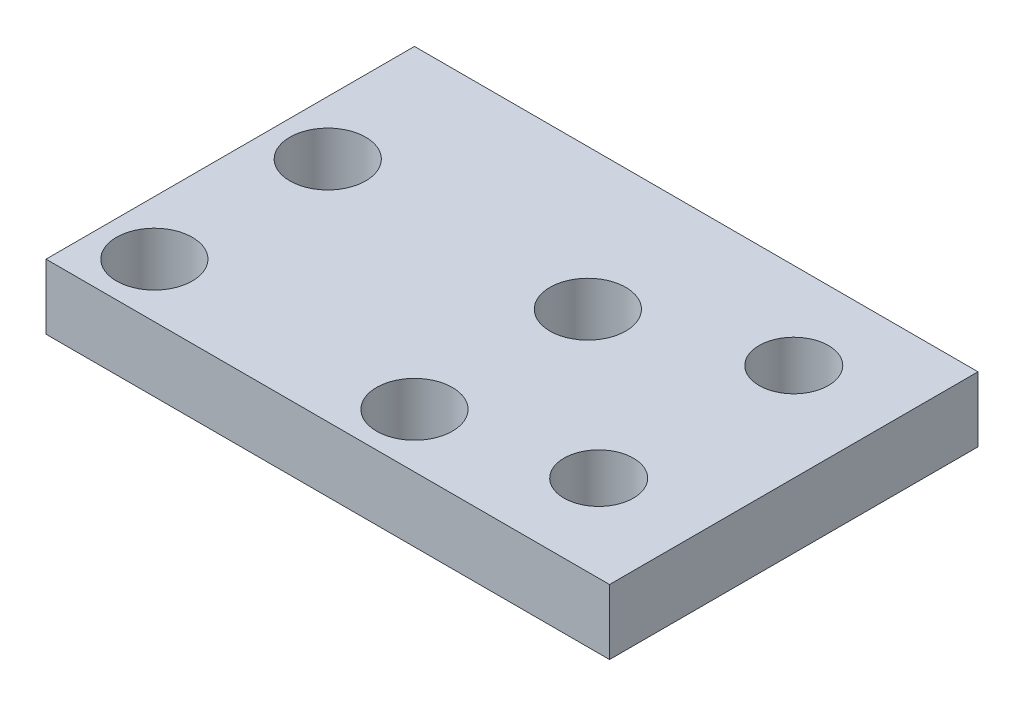
SolidWorks part; units mm, degrees
ref_plane "前视基准面" through (0, 0, 0) normal (0, 0, 1) x (1, 0, 0)
ref_plane "上视基准面" through (0, 0, 0) normal (0, 1, 0) x (1, 0, 0)
ref_plane "右视基准面" through (0, 0, 0) normal (1, 0, 0) x (0, 0, -1)
sketch "草图1" plane through (0, 0, 0) normal (0, 1, 0) x (1, 0, 0)
  line L0 (-5.8949, 6.5) -> (-34.2126, 6.5) construction
  line L1 (0, 0) -> (-26, 0)
  line L2 (0, 0) -> (0, 17)
  line L3 (0, 17) -> (-26, 17)
  line L4 (-26, 0) -> (-26, 17)
  line L5 (0, 8.5) -> (-28.0822, 8.5) construction
  circle A0 centre (-23.5, 10.5) radius 1.75
  circle A1 centre (-11.5, 10.5) radius 1.75
  circle A2 centre (-23.5, 2.5) radius 1.75
  circle A3 centre (-11.5, 2.5) radius 1.75
  circle A4 centre (-4.5, 13) radius 1.6
  circle A5 centre (-4.5, 4) radius 1.6
  point P21 (0, 0)
  dimension "D1" = 3.5
  dimension "D3" = 12
  dimension "D5" = 6.5
  dimension "D7" = 2.5
  dimension "D8" = 3.2
  dimension "D10" = 4.5
  dimension "D2" = 26
  dimension "D4" = 8
  dimension "D6" = 17
  dimension "D9" = 9
extrude "凸台-拉伸1" add sketch "草图1" along normal blind 3
